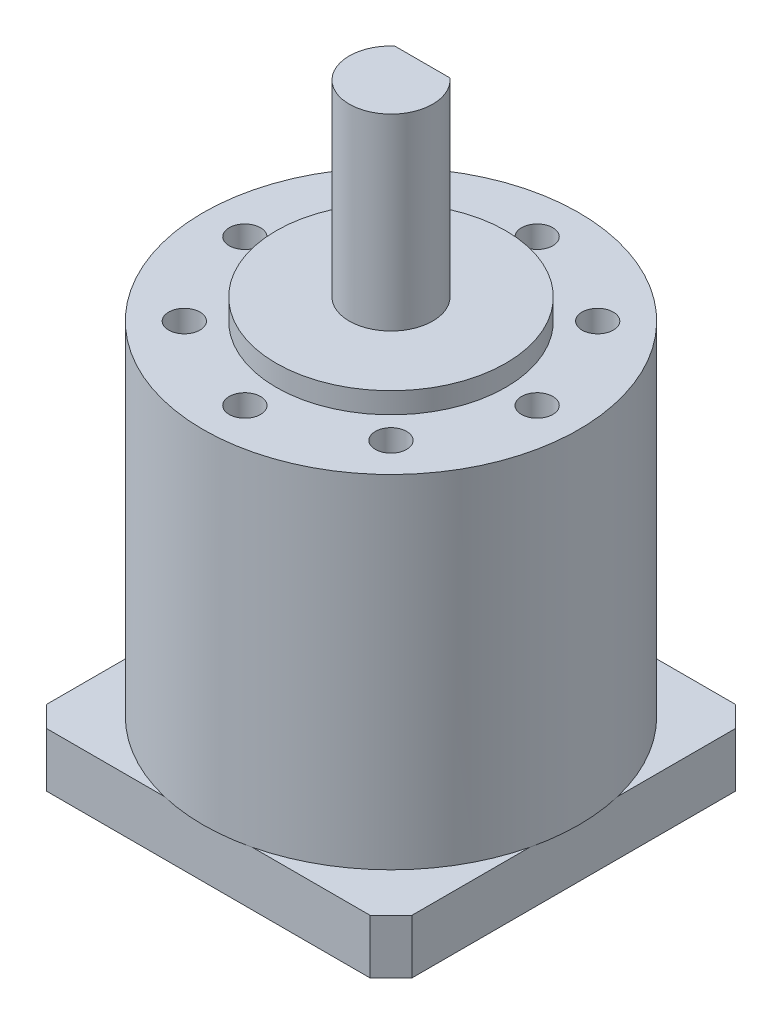
SolidWorks part; units mm, degrees
ref_plane "前视基准面" through (0, 0, 0) normal (0, 0, 1) x (1, 0, 0)
ref_plane "上视基准面" through (0, 0, 0) normal (0, 1, 0) x (1, 0, 0)
ref_plane "右视基准面" through (0, 0, 0) normal (1, 0, 0) x (0, 0, -1)
other "Configuration Table"
sketch "草图1" plane through (0, 0, 0) normal (0, 1, 0) x (1, 0, 0)
  line L1 (-17.5, 17.5) -> (17.5, 17.5)
  line L2 (-17.5, 17.5) -> (-17.5, -17.5)
  line L3 (-17.5, -17.5) -> (17.5, -17.5)
  line L4 (17.5, 17.5) -> (17.5, -17.5)
  line L5 (-17.5, 17.5) -> (17.5, -17.5) construction
  line L6 (-17.5, -17.5) -> (17.5, 17.5) construction
  point P0 (0, 0)
  dimension "D1" = 35
extrude "凸台-拉伸1" add sketch "草图1" along normal blind 5.2
sketch "草图2" plane through (0, 5.2, 0) normal (0, 1, 0) x (1, 0, 0)
  circle A0 centre (0, 0) radius 18
  dimension "D1" = 36
extrude "凸台-拉伸2" add sketch "草图2" along normal blind 32.8
sketch "草图3" plane through (0, 38, 0) normal (0, 1, 0) x (1, 0, 0)
  circle A0 centre (0, 0) radius 11
  dimension "D1" = 22
extrude "凸台-拉伸3" add sketch "草图3" along normal blind 2
sketch "草图4" plane through (0, 40, 0) normal (0, 1, 0) x (1, 0, 0)
  circle A0 centre (0, 0) radius 4
  dimension "D1" = 8
extrude "凸台-拉伸4" add sketch "草图4" along normal blind 18
sketch "草图5" plane through (0, 58, 0) normal (0, 1, 0) x (1, 0, 0)
  line L0 (0, 0) -> (0, 6.8831) construction
  line L2 (5.2734, 10.7663) -> (-5.2734, 10.7663)
  line L3 (5.2734, 10.7663) -> (5.2734, 3)
  line L4 (5.2734, 3) -> (-5.2734, 3)
  line L5 (-5.2734, 10.7663) -> (-5.2734, 3)
  line L6 (5.2734, 10.7663) -> (-5.2734, 3) construction
  line L7 (5.2734, 3) -> (-5.2734, 10.7663) construction
  dimension "D1" = 3
extrude "切除-拉伸1" cut sketch "草图5" against normal blind 15
chamfer "倒角1" distance 2 angle 45 4 edges at (17.5, 2.6, -17.5) (17.5, 2.6, 17.5) (-17.5, 2.6, 17.5) (-17.5, 2.6, -17.5)
sketch "草图6" plane through (0, 38, 0) normal (0, 1, 0) x (1, 0, 0)
  line L0 (0, 0) -> (0, 14) construction
  circle A0 centre (0, 0) radius 14 construction
  circle A1 centre (0, 14) radius 1.5
  circle A2 centre (14, 0) radius 1.5
  circle A3 centre (0, -14) radius 1.5
  circle A4 centre (-14, 0) radius 1.5
  point P14 (0, 0)
  dimension "D1" = 28
  dimension "D2" = 3
  dimension "D3" = 4
extrude "切除-拉伸2" cut sketch "草图6" against normal blind 6
sketch "草图7" plane through (0, 38, 0) normal (0, 1, 0) x (1, 0, 0)
  line L0 (0, 0) -> (-9.8995, 9.8995) construction
  line L1 (0, 0) -> (-14.3341, 0) construction
  circle A0 centre (-9.8995, 9.8995) radius 1.5
  circle A2 centre (9.8995, 9.8995) radius 1.5
  circle A3 centre (9.8995, -9.8995) radius 1.5
  circle A4 centre (-9.8995, -9.8995) radius 1.5
  point P5 (-9.8995, 9.8995)
  point P6 (13.6629, 12.7041)
  point P7 (0, 0)
  point P14 (0, 0)
  dimension "D3" = 3
  dimension "D1" = 45
  dimension "D2" = 14
  dimension "D4" = 4
extrude "切除-拉伸3" cut sketch "草图7" against normal blind 6
